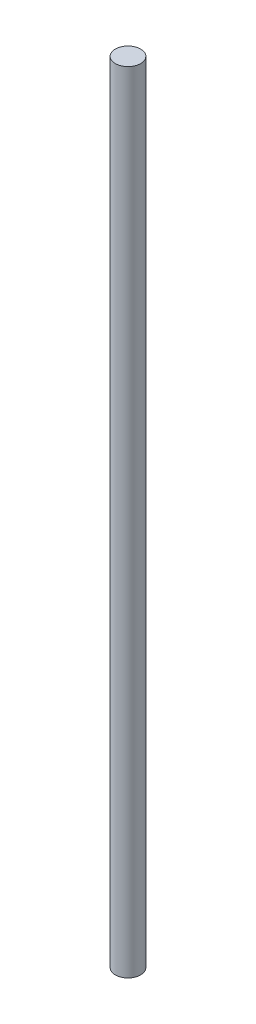
SolidWorks part; units mm, degrees
ref_plane "前视基准面" through (0, 0, 0) normal (0, 0, 1) x (1, 0, 0)
ref_plane "上视基准面" through (0, 0, 0) normal (0, 1, 0) x (1, 0, 0)
ref_plane "右视基准面" through (0, 0, 0) normal (1, 0, 0) x (0, 0, -1)
sketch "草图1" plane through (0, 0, 0) normal (0, 1, 0) x (1, 0, 0)
  circle A0 centre (0, 0) radius 4
extrude "凸台-拉伸1" add sketch "草图1" along normal blind 250
